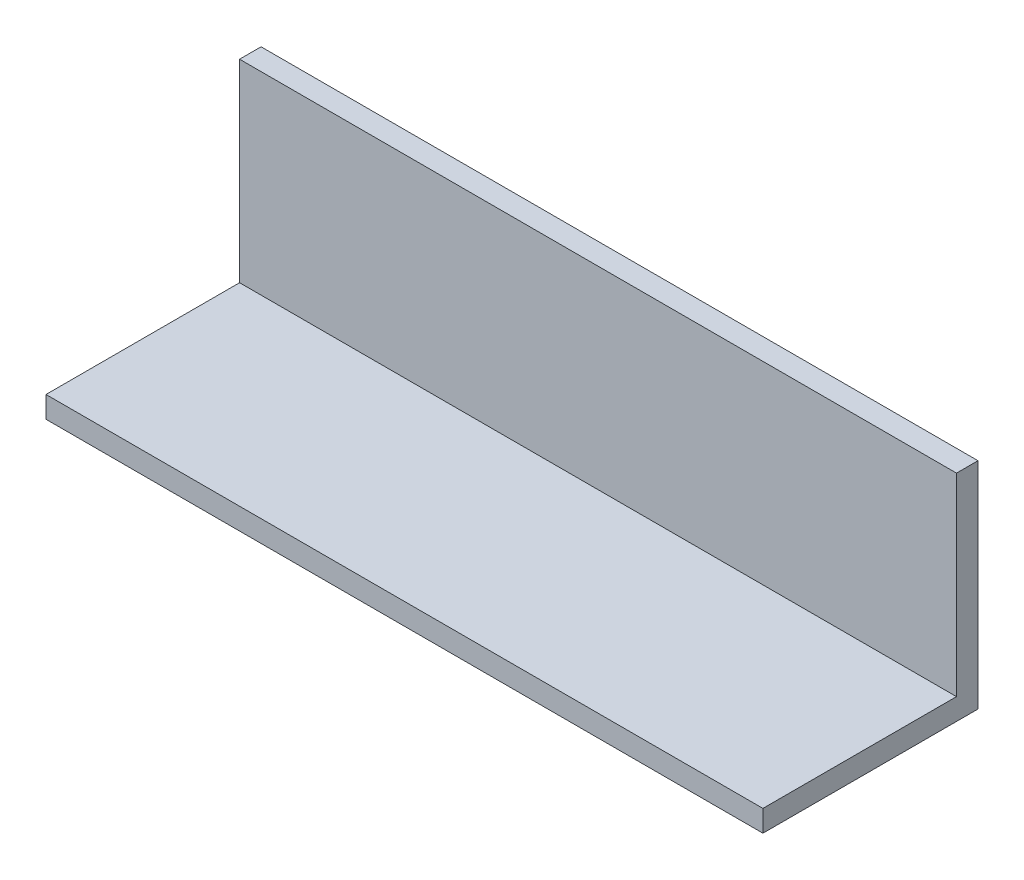
SolidWorks part; units mm, degrees
ref_plane "Alzado" through (0, 0, 0) normal (0, 0, 1) x (1, 0, 0)
ref_plane "Planta" through (0, 0, 0) normal (0, 1, 0) x (1, 0, 0)
ref_plane "Vista lateral" through (0, 0, 0) normal (1, 0, 0) x (0, 0, -1)
sketch "Croquis1" plane through (0, 0, 0) normal (1, 0, 0) x (0, 0, -1)
  line L1 (0, 0) -> (-15, 0)
  line L3 (-1.5, 1.5) -> (-15, 1.5)
  line L4 (-15, 0) -> (-15, 1.5)
  line L6 (0, 0) -> (0, 15)
  line L7 (0, 15) -> (-1.5, 15)
  line L8 (-1.5, 1.5) -> (-1.5, 15)
  dimension "D1" = 15
  dimension "D2" = 1.5
  dimension "D3" = 15
  dimension "D4" = 1.5
extrude "Saliente-Extruir1" add sketch "Croquis1" along normal blind 50
